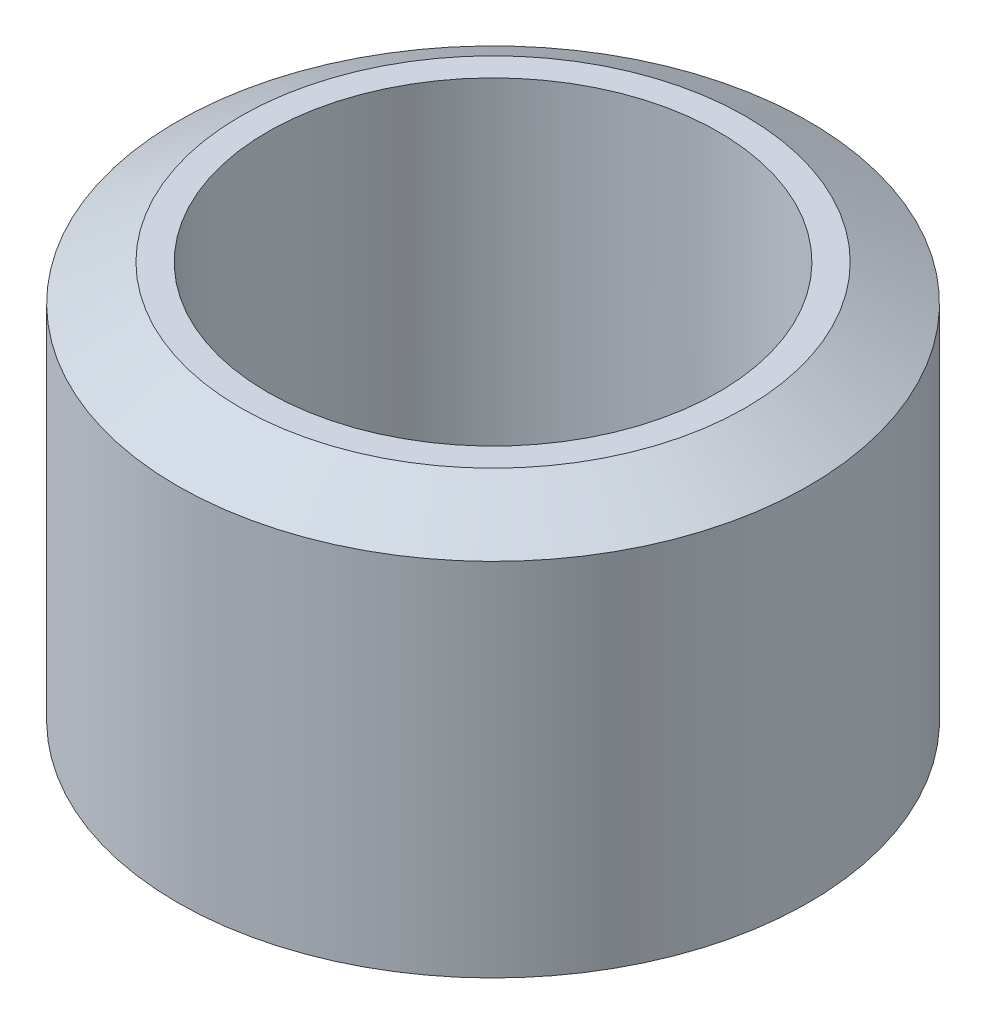
SolidWorks part; units mm, degrees
ref_plane "前视基准面" through (0, 0, 0) normal (0, 0, 1) x (1, 0, 0)
ref_plane "上视基准面" through (0, 0, 0) normal (0, 1, 0) x (1, 0, 0)
ref_plane "右视基准面" through (0, 0, 0) normal (1, 0, 0) x (0, 0, -1)
sketch "草图1" plane through (0, 0, 0) normal (0, 1, 0) x (1, 0, 0)
  circle A0 centre (0, 0) radius 8.75
  dimension "D1" = 17.5
extrude "凸台-拉伸1" add sketch "草图1" along normal blind 10
sketch "草图2" plane through (0, 10, 0) normal (0, 1, 0) x (1, 0, 0)
  circle A0 centre (0, 0) radius 6.25
  dimension "D1" = 12.5
extrude "切除-拉伸1" cut sketch "草图2" against normal up to next
sketch "草图3" plane through (0, 10, 0) normal (0, 1, 0) x (1, 0, 0)
  circle A0 centre (0, 0) radius 7
  circle A1 centre (0, 0) radius 6.25 construction
  circle A2 centre (0, 0) radius 6.25
  dimension "D1" = 14
extrude "凸台-拉伸2" add sketch "草图3" along normal blind 1
sketch "草图4" plane through (0, 0, 0) normal (0, -1, 0) x (1, 0, 0)
  circle A0 centre (0, 0) radius 7
  circle A1 centre (0, 0) radius 6.25 construction
  circle A2 centre (0, 0) radius 6.25
  dimension "D1" = 14
extrude "凸台-拉伸3" add sketch "草图4" along normal blind 1
sketch "草图5" plane through (0, 0, 0) normal (0, 0, 1) x (1, 0, 0)
  line L0 (0, 12.0964) -> (0, -2.0964) construction
  line L1 (-7, 11) -> (-8.75, 10)
  line L2 (-8.75, 10) -> (-7, 10)
  line L3 (-7, 10) -> (-7, 11)
  line L4 (-8.75, 0) -> (-7, 0)
  line L5 (-7, 0) -> (-7, -1)
  line L6 (-7, -1) -> (-8.75, 0)
revolve "旋转1" add sketch "草图5" angle 360 about L0
